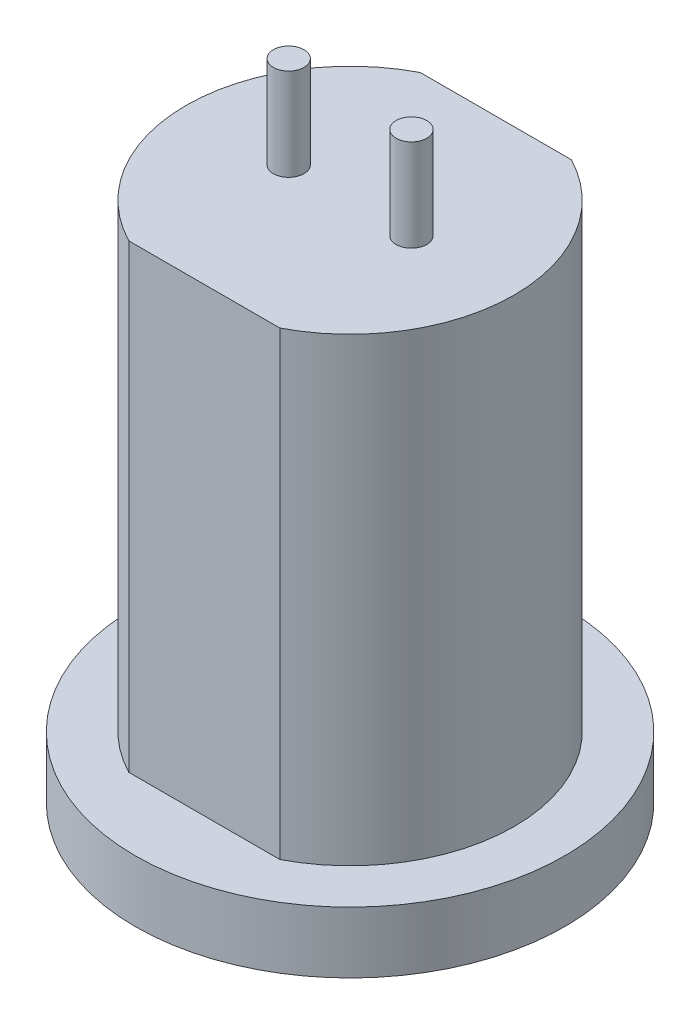
SolidWorks part; units mm, degrees
ref_plane "前视基准面" through (0, 0, 0) normal (0, 0, 1) x (1, 0, 0)
ref_plane "上视基准面" through (0, 0, 0) normal (0, 1, 0) x (1, 0, 0)
ref_plane "右视基准面" through (0, 0, 0) normal (1, 0, 0) x (0, 0, -1)
other "Configuration Table"
sketch "草图1" plane through (0, 0, 0) normal (0, 1, 0) x (1, 0, 0)
  circle A0 centre (0, 0) radius 7
  dimension "D1" = 14
extrude "凸台-拉伸1" add sketch "草图1" along normal blind 2
sketch "草图2" plane through (0, 2, 0) normal (0, 1, 0) x (1, 0, 0)
  line L0 (-2.4617, 4.75) -> (2.4617, 4.75)
  line L1 (-2.4617, -4.75) -> (2.4617, -4.75)
  line L2 (0, 0) -> (15.7559, 0) construction
  circle A0 centre (0, 0) radius 5.35
  dimension "D1" = 10.7
  dimension "D2" = 9.5
extrude "凸台-拉伸2" add sketch "草图2" along normal blind 15
sketch "草图3" plane through (0, 17, 0) normal (0, 1, 0) x (1, 0, 0)
  circle A0 centre (-2, 0) radius 0.5
  circle A1 centre (2, 0) radius 0.5
  dimension "D1" = 1
  dimension "D2" = 1
  dimension "D3" = 2
  dimension "D4" = 2
extrude "凸台-拉伸3" add sketch "草图3" along normal blind 3
sketch "草图4" plane through (0, 0, 0) normal (0, -1, 0) x (1, 0, 0)
  line L0 (-2.5, 0) -> (2.5, 0) construction
  line L1 (-2.5, 1.5) -> (2.5, 1.5)
  line L2 (-2.5, -1.5) -> (2.5, -1.5)
  arc A0 (-2.5, 1.5) -> (-2.5, -1.5) centre (-2.5, 0) ccw
  arc A1 (2.5, -1.5) -> (2.5, 1.5) centre (2.5, 0) ccw
  point P3 (0, 0)
  point P8 (-4, 0)
  point P9 (4, 0)
  dimension "D1" = 8
  dimension "D2" = 3
extrude "切除-拉伸1" cut sketch "草图4" against normal blind 5
